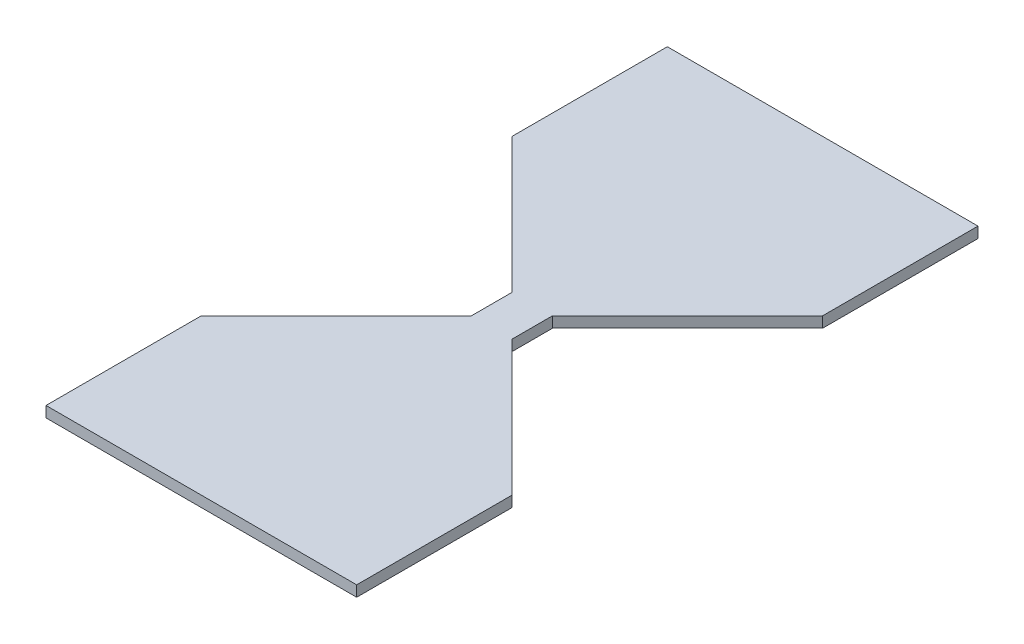
SolidWorks part; units mm, degrees
ref_plane "前视基准面" through (0, 0, 0) normal (0, 0, 1) x (1, 0, 0)
ref_plane "上视基准面" through (0, 0, 0) normal (0, 1, 0) x (1, 0, 0)
ref_plane "右视基准面" through (0, 0, 0) normal (1, 0, 0) x (0, 0, -1)
other "Configuration Table"
sketch "草图1" plane through (0, 0, 0) normal (0, 1, 0) x (1, 0, 0)
  line L0 (0, 0) -> (46, 0)
  line L1 (46, 0) -> (46, 23)
  line L2 (46, 23) -> (26.0002, 42.9998)
  line L3 (26.0002, 42.9998) -> (26.0002, 48.9998)
  line L4 (26.0002, 48.9998) -> (46, 68.9996)
  line L5 (46, 68.9996) -> (46, 91.9996)
  line L10 (19.9998, 42.9998) -> (0, 23)
  line L11 (0, 23) -> (0, 0)
  line L14 (19.9998, 42.9998) -> (19.9998, 48.9998)
  line L15 (19.9998, 48.9998) -> (0, 68.9996)
  line L16 (0, 68.9996) -> (0, 91.9996)
  line L17 (0, 91.9996) -> (46, 91.9996)
  point P18 (0, 0)
  point P19 (0, 0)
  point P21 (0, 0)
extrude "凸台-拉伸1" add sketch "草图1" along normal blind 1.6
